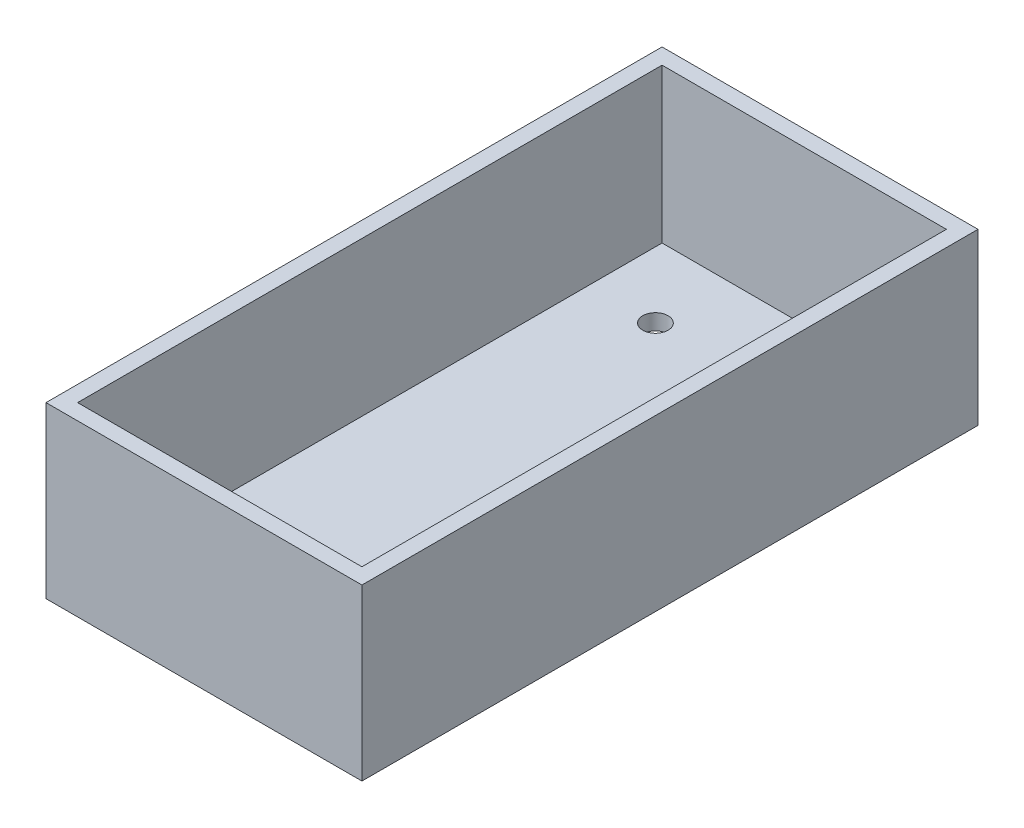
SolidWorks part; units mm, degrees
ref_plane "Front Plane" through (0, 0, 0) normal (0, 0, 1) x (1, 0, 0)
ref_plane "Top Plane" through (0, 0, 0) normal (0, 1, 0) x (1, 0, 0)
ref_plane "Right Plane" through (0, 0, 0) normal (1, 0, 0) x (0, 0, -1)
sketch "Эскиз1" plane through (0, 0, 0) normal (0, 1, 0) x (1, 0, 0)
  line L0 (0, 0) -> (0, 78)
  line L1 (0, 78) -> (40, 78)
  line L2 (40, 78) -> (40, 0)
  line L3 (40, 0) -> (0, 0)
extrude "Бобышка-Вытянуть1" add sketch "Эскиз1" along normal blind 21.5
sketch "Эскиз2" plane through (0, 21.5, 0) normal (0, 1, 0) x (1, 0, 0)
  line L0 (20, 78) -> (20, 74.8207) construction
  line L1 (40, 78) -> (0, 78) construction
  line L2 (20, 66.81) -> (29.65, 66.81) construction
  line L3 (20, 66.81) -> (10.35, 66.81) construction
  line L4 (0, 39) -> (40, 39) construction
  line L5 (0, 78) -> (0, 0) construction
  line L6 (40, 0) -> (40, 78) construction
  line L7 (20, 39) -> (20, 66.81) construction
  line L8 (20, 39) -> (20, 11.19) construction
  line L9 (20, 11.19) -> (10.35, 11.19) construction
  line L10 (20, 11.19) -> (29.65, 11.19) construction
  line L11 (0, 0) -> (40, 0) construction
  circle A0 centre (10.35, 66.81) radius 1.6
  circle A1 centre (29.65, 66.81) radius 1.6
  circle A2 centre (29.65, 11.19) radius 1.6
  circle A3 centre (10.35, 11.19) radius 1.6
  dimension "D1" = 3.2
  dimension "D2" = 10.35
  dimension "D3" = 11.19
shell "Оболочка1" thickness 2
extrude "Вырез-Вытянуть1" cut sketch "Эскиз2" against normal blind 40
